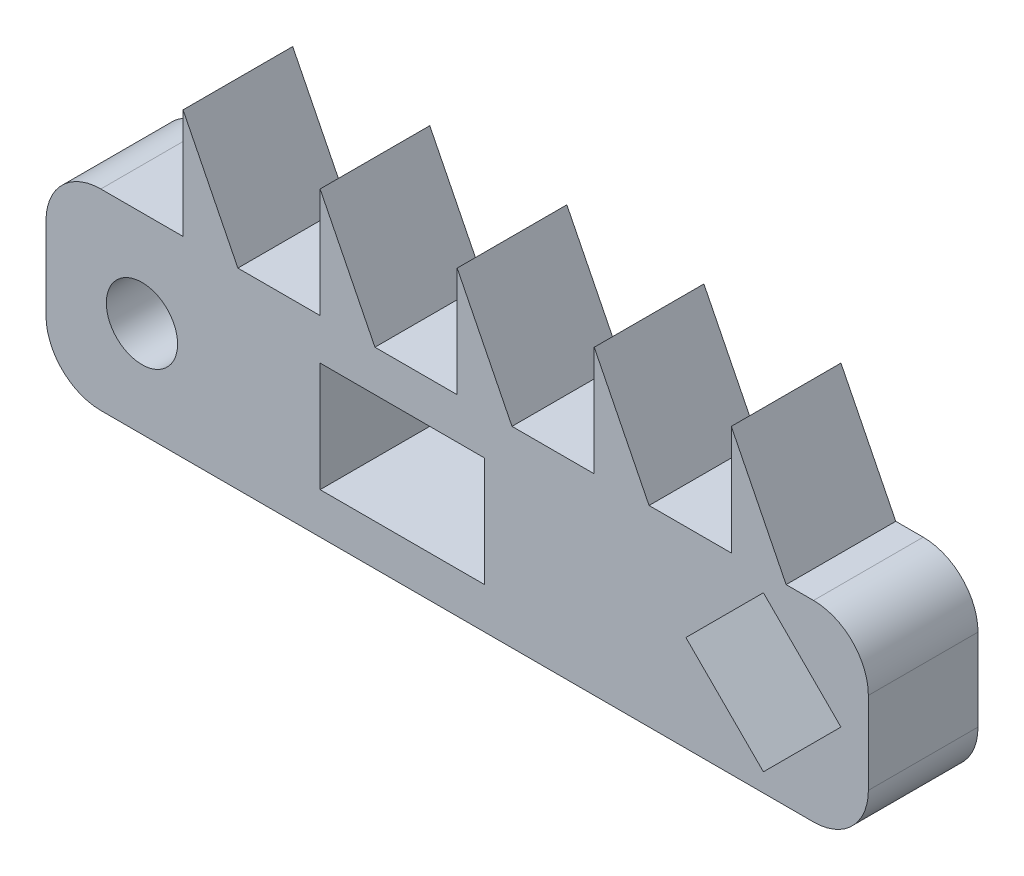
SolidWorks part; units mm, degrees
ref_plane "Спереди" through (0, 0, 0) normal (0, 0, 1) x (1, 0, 0)
ref_plane "Сверху" through (0, 0, 0) normal (0, 1, 0) x (1, 0, 0)
ref_plane "Справа" through (0, 0, 0) normal (1, 0, 0) x (0, 0, -1)
sketch "Эскиз1" plane through (0, 0, 0) normal (0, 0, 1) x (1, 0, 0)
  line L0 (23.3431, 3.5) -> (26.1716, 6.3284)
  line L1 (2, 0) -> (28, 0)
  line L2 (0, 2) -> (0, 5)
  line L3 (2, 7) -> (28, 7)
  line L4 (30, 2) -> (30, 5)
  line L5 (10, 5.5) -> (16, 5.5)
  line L6 (10, 5.5) -> (10, 1.5)
  line L7 (10, 1.5) -> (16, 1.5)
  line L8 (16, 5.5) -> (16, 1.5)
  line L9 (26.1716, 6.3284) -> (29, 3.5)
  line L10 (29, 3.5) -> (26.1716, 0.6716)
  line L11 (26.1716, 0.6716) -> (23.3431, 3.5)
  line L12 (26.1716, 6.3284) -> (26.1716, 7) construction
  line L13 (26.1716, 0.6716) -> (26.1716, 0) construction
  circle A0 centre (3.5, 3.5) radius 1.3
  arc A1 (28, 7) -> (30, 5) centre (28, 5) cw
  arc A2 (0, 5) -> (2, 7) centre (2, 5) cw
  arc A3 (2, 0) -> (0, 2) centre (2, 2) cw
  arc A4 (28, 0) -> (30, 2) centre (28, 2) ccw
  point P7 (10, 3.5)
  point P8 (0, 3.5)
  point P21 (30, 7)
  point P24 (0, 7)
  point P27 (0, 0)
  dimension "D1" = 2.6
  dimension "D12" = 2
  dimension "D13" = 2
  dimension "D2" = 7
  dimension "D3" = 3.5
  dimension "D4" = 4
  dimension "D5" = 6
  dimension "D6" = 10
  dimension "D7" = 30
  dimension "D8" = 45
  dimension "D9" = 1
  dimension "D10" = 4
  dimension "D11" = 4
extrude "Бобышка-Вытянуть1" add sketch "Эскиз1" along normal blind 4
sketch "Эскиз2" plane through (0, 0, 4) normal (0, 0, 1) x (1, 0, 0)
  line L0 (5, 7) -> (5, 11)
  line L1 (28, 7) -> (2, 7) construction
  line L2 (5, 11) -> (7, 7)
  line L3 (7, 7) -> (5, 7)
  line L4 (10, 7) -> (10, 11)
  line L5 (10, 11) -> (12, 7)
  line L6 (12, 7) -> (10, 7)
  line L7 (15, 7) -> (15, 11)
  line L8 (15, 11) -> (17, 7)
  line L9 (17, 7) -> (15, 7)
  line L10 (20, 7) -> (20, 11)
  line L11 (20, 11) -> (22, 7)
  line L12 (22, 7) -> (20, 7)
  line L13 (25, 7) -> (25, 11)
  line L14 (25, 11) -> (27, 7)
  line L15 (27, 7) -> (25, 7)
  dimension "D1" = 4
  dimension "D2" = 2
  dimension "D3" = 3
  dimension "D4" = 5
extrude "Бобышка-Вытянуть2" add sketch "Эскиз2" against normal blind 4
